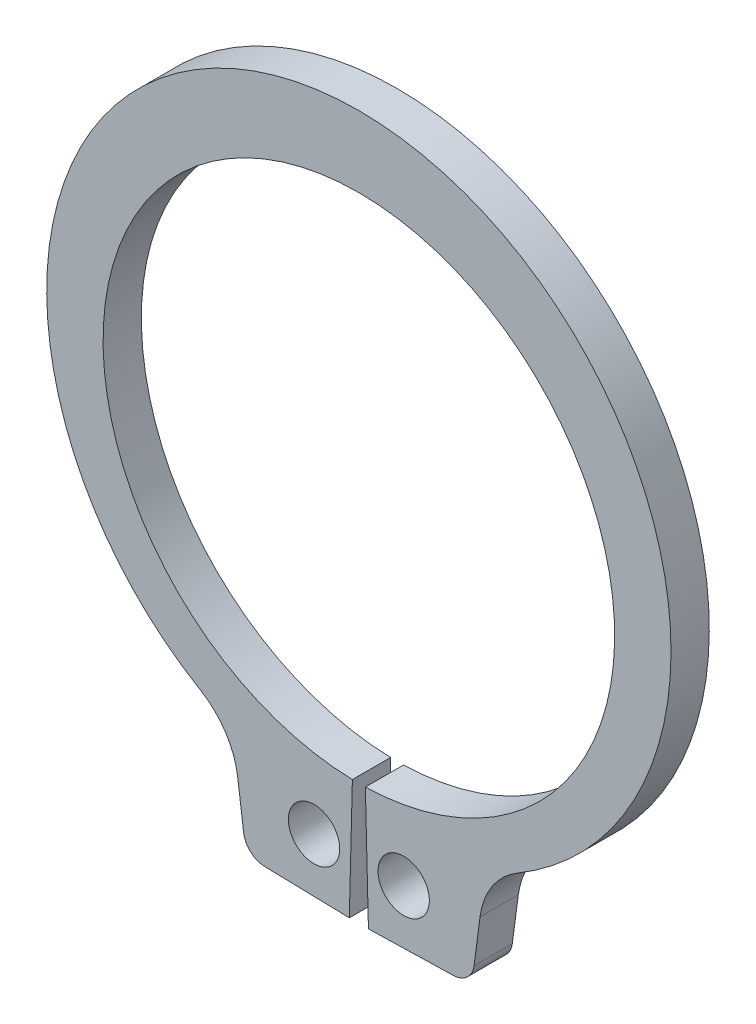
SolidWorks part; units mm, degrees
material "AISI 1020 Steel, Cold Rolled"
ref_plane "Plane1" through (0, 0, 0) normal (0, 0, 1) x (1, 0, 0)
ref_plane "Plane2" through (0, 0, 0) normal (0, 1, 0) x (1, 0, 0)
ref_plane "Plane3" through (0, 0, 0) normal (1, 0, 0) x (0, 0, -1)
sketch "Clipboard" plane through (0, 0, 0) normal (0, 0, 1) x (1, 0, 0)
  line L0 (0, 0) -> (1.651, 0)
  line L1 (0, 0) -> (0, 1.016)
  line L2 (0, 0) -> (0, -2.8194)
  circle A0 centre (0, 0) radius 0.5969
  circle A1 centre (0, 0) radius 6.35
  dimension "HoleDia" = 1.1938
  dimension "ShaftDia" = 12.7
  dimension "LargeSection" = 1.651
  dimension "SmallSection" = 1.016
  dimension "LugSection" = 2.8194
sketch "BodySke" plane through (0, 0, 0) normal (0, 0, 1) x (1, 0, 0)
  line L0 (-1.5431, 0) -> (1.5431, 0) construction
  line L1 (0, 0) -> (0, 7.5946) construction
  line L2 (0.1507, -5.9417) -> (0.2223, -8.7602)
  line L3 (-0.1507, -5.9417) -> (-0.2223, -8.7602)
  line L4 (0, 0) -> (4.6029, -7.4568) construction
  line L5 (0, 0) -> (-4.6029, -7.4568) construction
  line L6 (0.2223, -8.7602) -> (2.1935, -8.7102)
  line L7 (2.8153, -7.2215) -> (2.6765, -8.2756)
  line L8 (-2.8153, -7.2215) -> (-2.6765, -8.2756)
  line L9 (-0.2223, -8.7602) -> (-2.1935, -8.7102)
  circle A0 centre (0, 0) radius 5.9436 construction
  arc A1 (0.1507, -5.9417) -> (-0.1507, -5.9417) centre (0, 0) ccw
  arc A2 (3.6556, -5.9222) -> (-3.6556, -5.9222) centre (0, 0.3419) ccw construction
  arc A3 (0.2223, -8.7602) -> (2.1944, -8.4838) centre (0, 0) ccw construction
  arc A4 (3.6864, -5.9041) -> (2.8153, -7.2215) centre (4.6029, -7.4568) ccw
  arc A5 (-2.8153, -7.2215) -> (-3.6864, -5.9041) centre (-4.6029, -7.4568) ccw
  arc A6 (-2.1944, -8.4838) -> (-0.2223, -8.7602) centre (0, 0) ccw construction
  arc A7 (3.6864, -5.9041) -> (-3.6864, -5.9041) centre (0, 0.3419) ccw
  arc A8 (-2.8444, -7.0007) -> (2.8444, -7.0007) centre (0, 0) ccw construction
  circle A9 centre (1.0414, -7.4844) radius 0.5969
  circle A10 centre (-1.0414, -7.4844) radius 0.5969
  arc A11 (2.6765, -8.2756) -> (2.1935, -8.7102) centre (2.1808, -8.2103) cw
  arc A12 (-2.6765, -8.2756) -> (-2.1935, -8.7102) centre (-2.1808, -8.2103) ccw
  point P28 (2.6671, -8.3473)
  point P31 (-2.6671, -8.3473)
  dimension "GrooveDia" = 11.8872
  dimension "LugRad" = 8.763
  dimension "HoleOffsetRad" = 7.5565
  dimension "HoleDia" = 1.1938
  dimension "D3" = 0.5
  dimension "LargeRad" = 7.5946
  dimension "SmallRad" = 6.9596
  dimension "SmallAngle" = 63.371
  dimension "D2" = 15
  dimension "HoleSpacing" = 2.0828
  dimension "Gap" = 0.4445
extrude "Body" add sketch "BodySke" against normal blind 0.889
equation "' \"ShaftDia@Clipboard\" = 4"
equation "' \"Thickness@Body\" = 0.25"
equation "' \"GrooveDia@BodySke\" = 3.8"
equation "' \"LugSection@Clipboard\" = 1.35"
equation "' \"LargeSection@Clipboard\" = 0.65"
equation "' \"SmallSection@Clipboard\" = 0.4"
equation "' \"HoleDia@Clipboard\" = 0.6"
equation "' \"ShaftDia@Clipboard\" = 15"
equation "' \"Thickness@Body\" = 0.9"
equation "' \"GrooveDia@BodySke\" = 14.15"
equation "' \"LugSection@Clipboard\" = 2.8"
equation "' \"LargeSection@Clipboard\" = 1.8"
equation "' \"SmallSection@Clipboard\" = 1.05"
equation "' \"HoleDia@Clipboard\" = 1.2"
equation "\"Gap@BodySke\" =  \"Thickness@Body\" / 2"
equation "\"LargeRad@BodySke\" =  \"GrooveDia@BodySke\" / 2 +  \"LargeSection@Clipboard\""
equation "\"SmallRad@BodySke\" =  \"GrooveDia@BodySke\" / 2 +  \"SmallSection@Clipboard\""
equation "\"LugRad@BodySke\" = \"GrooveDia@BodySke\" / 2 + \"LugSection@Clipboard\""
equation "\"HoleOffsetRad@BodySke\" = (  \"ShaftDia@Clipboard\" / 2 + \"LugRad@BodySke\" ) / 2"
equation "\"HoleSpacing@BodySke\" = \"Gap@BodySke\"  * 2 +  \"HoleDia@Clipboard\""
equation "\"HoleDia@BodySke\" =  \"HoleDia@Clipboard\""
equation "\"SmallAngle@BodySke\" = atn(\"HoleSpacing@BodySke\" / 2 / sqr(\"HoleOffsetRad@BodySke\"  * \"HoleOffsetRad@BodySke\" - (\"HoleSpacing@BodySke\" / 2) * (\"HoleSpacing@BodySke\" / 2) ))  * 8 * ( 180 / 3.141593)"
